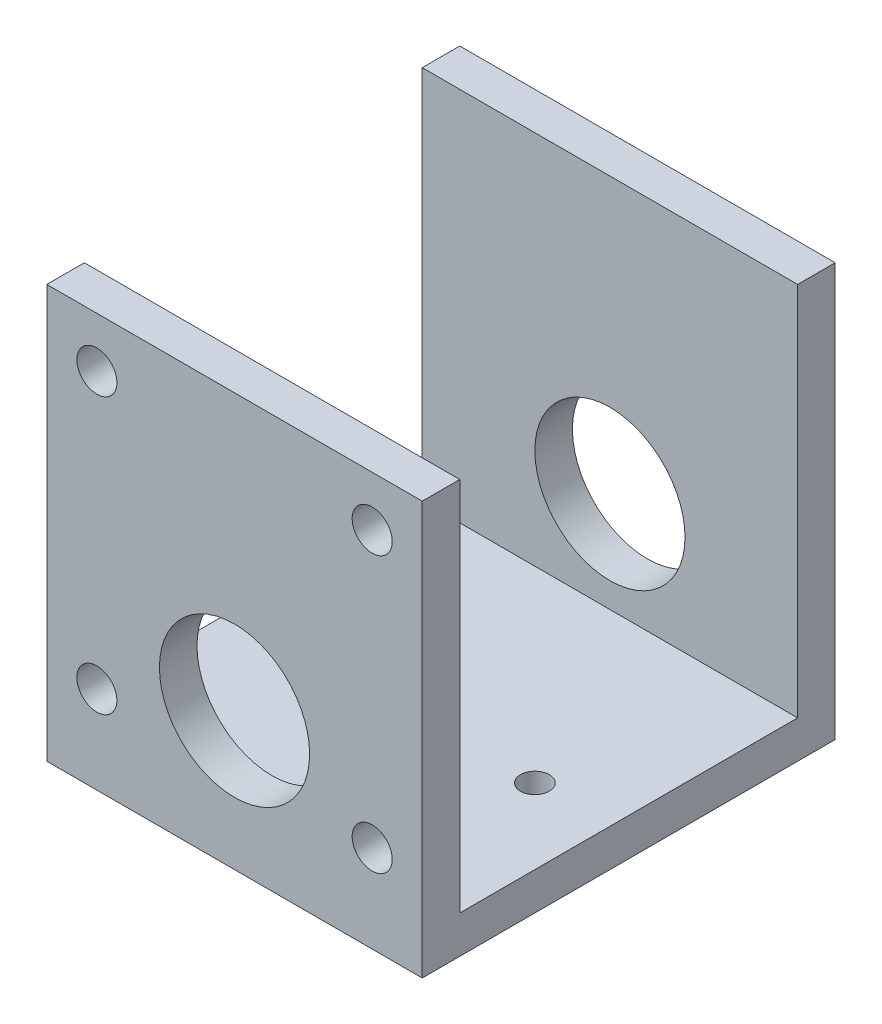
SolidWorks part; units mm, degrees
ref_plane "Front Plane" through (0, 0, 0) normal (0, 0, 1) x (1, 0, 0)
ref_plane "Top Plane" through (0, 0, 0) normal (0, 1, 0) x (1, 0, 0)
ref_plane "Right Plane" through (0, 0, 0) normal (1, 0, 0) x (0, 0, -1)
sketch "Sketch1" plane through (0, 0, 0) normal (0, 1, 0) x (1, 0, 0)
  line L1 (0, 0) -> (30, 0)
  line L2 (0, 0) -> (0, 30)
  line L3 (0, 30) -> (30, 30)
  line L4 (30, 0) -> (30, 30)
  circle A0 centre (6, 12) radius 1.15
  circle A1 centre (24, 12) radius 1.15
  dimension "D2" = 2.3
  dimension "D3" = 2.3
  dimension "D4" = 18
  dimension "D7" = 18
  dimension "D1" = 30
  dimension "D5" = 6
  dimension "D6" = 30
extrude "Boss-Extrude1" add sketch "Sketch1" along normal blind 3
sketch "Sketch2" plane through (0, 3, 0) normal (0, 1, 0) x (1, 0, 0)
  line L0 (0, 30) -> (0, 0) construction
  line L1 (30, 30) -> (0, 30)
  line L2 (30, 30) -> (30, 27)
  line L3 (30, 27) -> (0, 27)
  line L4 (0, 30) -> (0, 27)
  dimension "D1" = 3
extrude "Boss-Extrude2" add sketch "Sketch2" along normal blind 30
sketch "Sketch3" plane through (0, 0, -30) normal (0, 0, -1) x (-1, 0, 0)
  line L0 (-30, 0) -> (0, 0) construction
  line L1 (-30, 33) -> (-30, 0) construction
  circle A0 centre (-15, 11) radius 6
  dimension "D1" = 11
  dimension "D2" = 12
  dimension "D3" = 15
extrude "Cut-Extrude1" cut sketch "Sketch3" against normal up to next
sketch "Sketch4" plane through (0, 0, 0) normal (0, 0, 1) x (1, 0, 0)
  line L1 (30, 0) -> (0, 0)
  line L2 (30, 0) -> (30, 33)
  line L3 (30, 33) -> (0, 33)
  line L4 (0, 0) -> (0, 33)
  circle A0 centre (15, 11) radius 6
  dimension "D2" = 12
  dimension "D1" = 33
extrude "Boss-Extrude3" add sketch "Sketch4" along normal blind 3
sketch "Sketch5" plane through (0, 0, 3) normal (0, 0, 1) x (1, 0, 0)
  line L0 (30, 0) -> (30, 33) construction
  line L1 (26, 7) -> (4, 7) construction
  line L2 (26, 7) -> (26, 29) construction
  line L3 (26, 29) -> (4, 29) construction
  line L4 (4, 7) -> (4, 29) construction
  line L5 (0, 0) -> (30, 0) construction
  circle A0 centre (26, 7) radius 1.6
  circle A1 centre (4, 7) radius 1.6
  circle A2 centre (4, 29) radius 1.6
  circle A3 centre (26, 29) radius 1.6
  dimension "D5" = 3.2
  dimension "D6" = 3.2
  dimension "D7" = 3.2
  dimension "D8" = 3.2
  dimension "D1" = 22
  dimension "D2" = 4
  dimension "D3" = 22
  dimension "D4" = 7
extrude "Cut-Extrude3" cut sketch "Sketch5" against normal up to next
